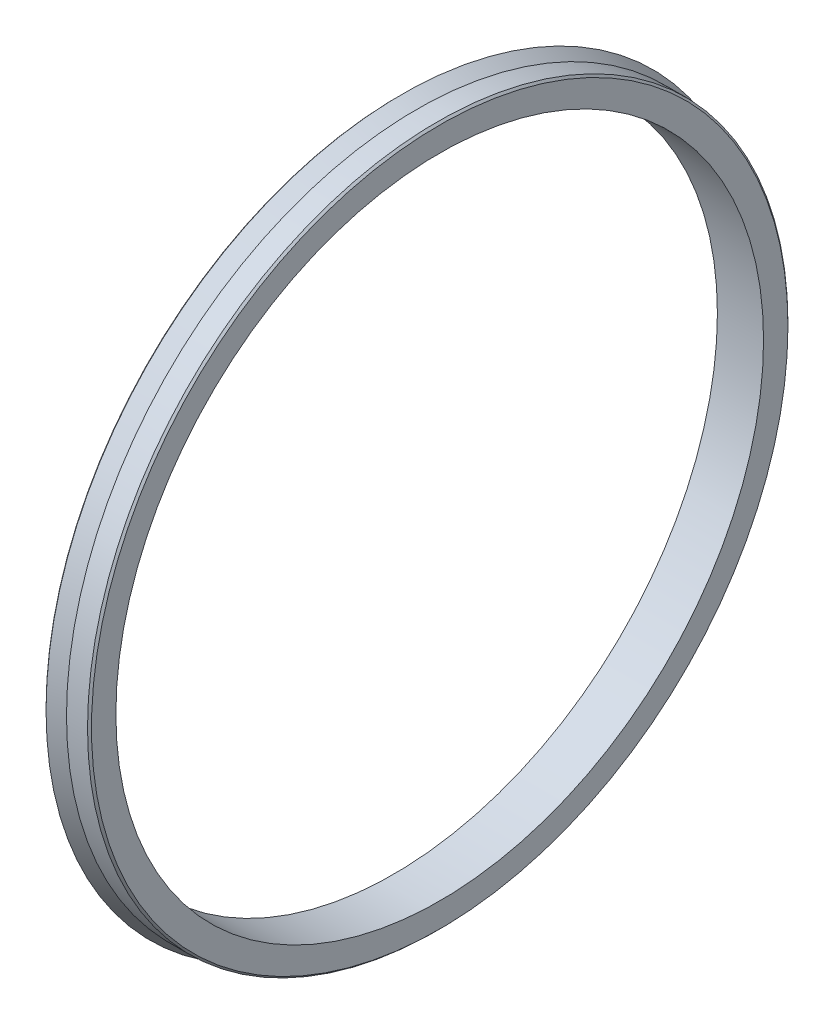
SolidWorks part; units mm, degrees
ref_plane "Front Plane" through (0, 0, 0) normal (0, 0, 1) x (1, 0, 0)
ref_plane "Top Plane" through (0, 0, 0) normal (0, 1, 0) x (1, 0, 0)
ref_plane "Right Plane" through (0, 0, 0) normal (1, 0, 0) x (0, 0, -1)
sketch "Sketch1" plane through (0, 0, 0) normal (0, 0, 1) x (1, 0, 0)
  line L9 (0, 0) -> (7, 0)
  line L10 (7, 0) -> (7, 4)
  line L11 (7, 4) -> (3.51, 4)
  line L12 (0, 0) -> (0, 1)
  line L15 (1, 4.89) -> (1, 4.3766)
  line L16 (1.3175, 3.9111) -> (4.292, 2.7448)
  line L17 (5.0535, 2.4462) -> (1.9084, 2.4462) construction
  line L18 (7, 2) -> (-3.6894, 2) construction
  line L19 (0, 1) -> (4, 1.2)
  line L20 (7, 0) -> (7, -49.11)
  line L21 (7, -49.11) -> (-15.456, -49.11) construction
  line L22 (3.51, 4) -> (1, 4.89)
  arc A0 (1, 4.3766) -> (1.3175, 3.9111) centre (1.5, 4.3766) ccw
  arc A1 (4, 1.2) -> (4.292, 2.7448) centre (4, 2) ccw
  dimension "D1" = 7
  dimension "D10" = 0.5
  dimension "D11" = 1.6
  dimension "D2" = 4
  dimension "D3" = 3.49
  dimension "D4" = 1
  dimension "D5" = 6
  dimension "D8" = 4.89
  dimension "D9" = 21.41
  dimension "D12" = 3
  dimension "D13" = 49.11
revolve "Revolve2" add sketch "Sketch1" angle 360 about L21
chamfer "Chamfer1" distance 0.3 angle 45 1 edges at (7, -49.11, -53.11)
chamfer "Chamfer2" distance 0.3 angle 45 1 edges at (1, -49.11, -54)
